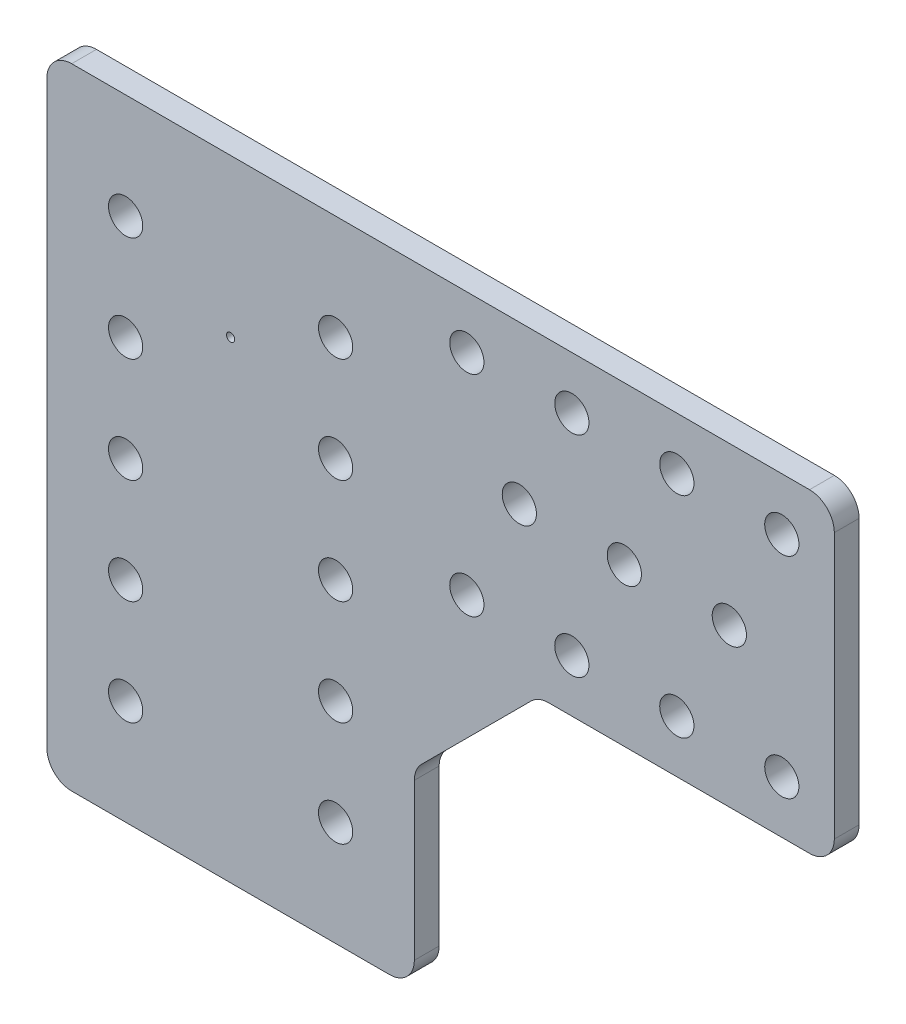
SolidWorks part; units mm, degrees
ref_plane "Front Plane" through (0, 0, 0) normal (0, 0, 1) x (1, 0, 0)
ref_plane "Top Plane" through (0, 0, 0) normal (0, 1, 0) x (1, 0, 0)
ref_plane "Right Plane" through (0, 0, 0) normal (1, 0, 0) x (0, 0, -1)
sketch "Sketch1" plane through (0, 0, 0) normal (0, 0, 1) x (1, 0, 0)
  line L0 (0, 0) -> (50.8, 0)
  line L1 (50.8, 0) -> (50.8, 38.1)
  line L2 (50.8, 38.1) -> (-44.45, 38.1)
  line L3 (-44.45, 38.1) -> (-44.45, -38.1)
  line L4 (-44.45, -38.1) -> (0, -38.1)
  line L5 (0, -38.1) -> (0, 0)
  line L6 (50.8, 0) -> (0, -38.1) construction
  line L7 (-22.225, -38.1) -> (-22.225, 38.1) construction
  line L8 (50.8, 19.05) -> (-22.225, 19.05) construction
  line L9 (44.45, 38.1) -> (44.45, 31.75) construction
  line L10 (44.45, 31.75) -> (50.8, 31.75) construction
  line L11 (6.35, 45.0611) -> (44.45, 45.0611) construction
  line L12 (25.4, 45.0611) -> (25.4, 19.05) construction
  circle A0 centre (-22.225, 19.05) radius 0.5
  circle A1 centre (44.45, 31.75) radius 2.07
  circle A2 centre (31.75, 31.75) radius 2.07
  circle A3 centre (19.05, 31.75) radius 2.07
  circle A4 centre (6.35, 31.75) radius 2.07
  circle A5 centre (6.35, 6.35) radius 2.07
  circle A6 centre (19.05, 6.35) radius 2.07
  circle A7 centre (31.75, 6.35) radius 2.07
  circle A8 centre (44.45, 6.35) radius 2.07
  circle A9 centre (25.4, 19.05) radius 2.07
  circle A10 centre (38.1, 19.05) radius 2.07
  circle A11 centre (12.7, 19.05) radius 2.07
  circle A12 centre (-34.925, -25.4) radius 2.07
  circle A13 centre (-9.525, -25.4) radius 2.07
  circle A14 centre (-34.925, -12.7) radius 2.07
  circle A15 centre (-9.525, -12.7) radius 2.07
  circle A16 centre (-34.925, 0) radius 2.07
  circle A17 centre (-9.525, 0) radius 2.07
  circle A18 centre (-34.925, 12.7) radius 2.07
  circle A19 centre (-9.525, 12.7) radius 2.07
  circle A20 centre (-34.925, 25.4) radius 2.07
  circle A21 centre (-9.525, 25.4) radius 2.07
  point P37 (25.4, 45.0611)
  dimension "D5" = 1
  dimension "D7" = 4.14
  dimension "D10" = 2
  dimension "D1" = 38.1
  dimension "D2" = 50.8
  dimension "D3" = 44.45
  dimension "D4" = 76.2
  dimension "D6" = 6.35
  dimension "D9" = 12.7
  dimension "D11" = 12.7
  dimension "D12" = 12.7
  dimension "D13" = 12.7
  dimension "D15" = 25.4
  dimension "D17" = 12.7
  dimension "D8" = 4
  dimension "D14" = 2
  dimension "D16" = 5
extrude "Boss-Extrude1" add sketch "Sketch1" along normal mid plane 3
fillet "Fillet1" radius 3 5 edges at (-44.45, -38.1, 0) (50.8, 38.1, 0) (-44.45, 38.1, 0) (50.8, 0, 0) (0, -38.1, 0)
chamfer "Chamfer1" distance 15 angle 45 1 edges at (0, 0, 0)
fillet "Fillet2" radius 3 2 edges at (0, -15, 0) (15, 0, 0)
